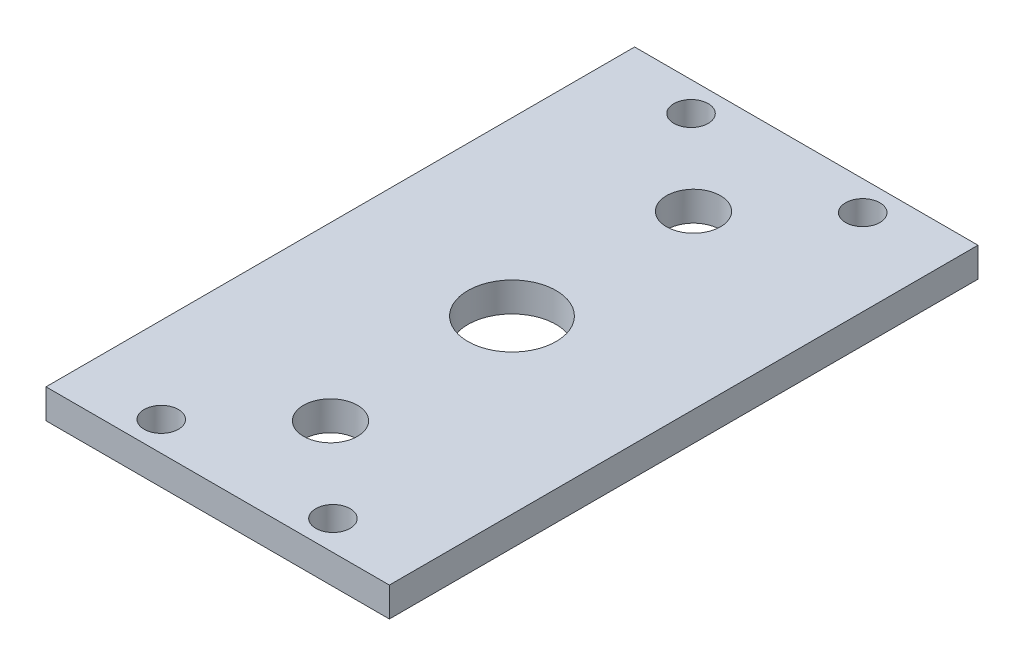
SolidWorks part; units mm, degrees
material "Thornel Mat VMA"
ref_plane "前视基准面" through (0, 0, 0) normal (0, 0, 1) x (1, 0, 0)
ref_plane "上视基准面" through (0, 0, 0) normal (0, 1, 0) x (1, 0, 0)
ref_plane "右视基准面" through (0, 0, 0) normal (1, 0, 0) x (0, 0, -1)
sketch "草图1" plane through (0, 0, 0) normal (0, 1, 0) x (1, 0, 0)
  line L1 (-17.5, -30) -> (17.5, -30)
  line L2 (-17.5, -30) -> (-17.5, 30)
  line L3 (-17.5, 30) -> (17.5, 30)
  line L4 (17.5, -30) -> (17.5, 30)
  line L5 (-17.5, -30) -> (17.5, 30) construction
  line L6 (-17.5, 30) -> (17.5, -30) construction
  point P0 (0, 0)
  dimension "D1" = 35
  dimension "D2" = 60
extrude "凸台-拉伸1" add sketch "草图1" along normal blind 3
sketch "草图2" plane through (0, 3, 0) normal (0, 1, 0) x (1, 0, 0)
  line L0 (17.5, -30) -> (17.5, 30) construction
  line L1 (-17.5, -30) -> (17.5, -30)
  line L2 (-17.5, -30) -> (-17.5, -24)
  line L3 (-17.5, -24) -> (17.5, -24)
  line L4 (17.5, -30) -> (17.5, -24)
  line L5 (-17.5, 30) -> (-17.5, -30) construction
  line L6 (17.5, 30) -> (-17.5, 30)
  line L7 (17.5, 30) -> (17.5, 24)
  line L8 (17.5, 24) -> (-17.5, 24)
  line L9 (-17.5, 30) -> (-17.5, 24)
  line L10 (-17.5, 27) -> (17.5, 27)
  line L11 (17.5, -27) -> (-17.5, -27)
  line L12 (0, -27) -> (17.5, -27)
  line L13 (0, -27) -> (-17.5, -27)
  point P19 (8.75, -27)
  point P20 (-8.75, -27)
  point P21 (-8.75, 27)
  point P22 (8.75, 27)
  dimension "D1" = 6
  dimension "D2" = 6
  dimension "D3" = 8.75
  dimension "D4" = 8.75
sketch "草图3" plane through (0, 3, 0) normal (0, 1, 0) x (1, 0, 0)
  point P0 (-8.75, 27)
  point P3 (8.75, 27)
  point P6 (8.75, -27)
  point P9 (-8.75, -27)
hole_wizard "孔1" positions "草图3" profile "草图4" legacy end condition up to next
sketch "草图4" plane through (-8.75, 3, -27) normal (1, 0, 0) x (0, 0, 1)
  line L0 (0, 0) -> (0, 3)
  line L1 (0, 3) -> (1.75, 3)
  line L2 (1.75, 3) -> (1.75, 0)
  line L3 (1.75, 0) -> (0, 0)
  line L4 (0, 110) -> (0, -10) construction
  dimension "直径" = 3.5
  dimension "深度" = 3
sketch "草图5" plane through (0, 3, 0) normal (0, 1, 0) x (1, 0, 0)
  line L0 (0, 0) -> (0, 18.5)
  line L1 (0, 0) -> (0, -18.5)
  dimension "D1" = 18.5
  dimension "D2" = 18.5
sketch "草图6" plane through (0, 3, 0) normal (0, 1, 0) x (1, 0, 0)
  point P0 (0, 18.5)
  point P3 (0, -18.5)
hole_wizard "孔2" positions "草图6" profile "草图7" legacy end condition up to next
sketch "草图7" plane through (0, 3, -18.5) normal (1, 0, 0) x (0, 0, 1)
  line L0 (0, 0) -> (0, 3)
  line L1 (0, 3) -> (2.75, 3)
  line L2 (2.75, 3) -> (2.75, 0)
  line L3 (2.75, 0) -> (0, 0)
  line L4 (0, 110) -> (0, -10) construction
  dimension "直径" = 5.5
  dimension "深度" = 3
sketch "草图8" plane through (0, 3, 0) normal (0, 1, 0) x (1, 0, 0)
  circle A0 centre (0, 0) radius 4.5
  dimension "D1" = 9
extrude "切除-拉伸1" cut sketch "草图8" against normal blind 3
